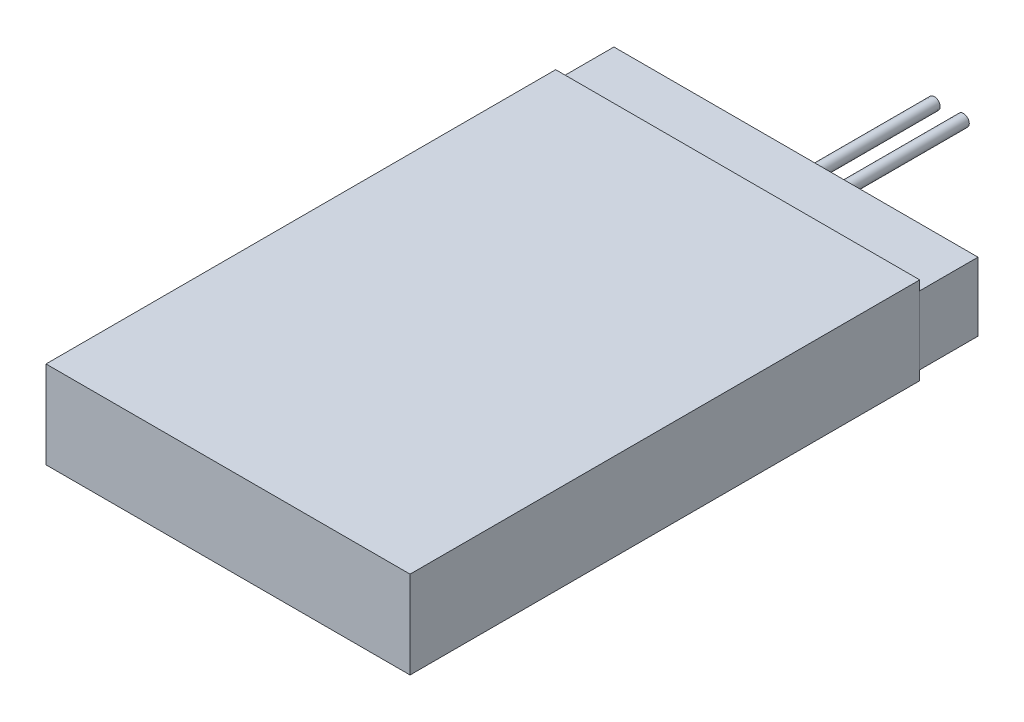
SolidWorks part; units mm, degrees
ref_plane "Front Plane" through (0, 0, 0) normal (0, 0, 1) x (1, 0, 0)
ref_plane "Top Plane" through (0, 0, 0) normal (0, 1, 0) x (1, 0, 0)
ref_plane "Right Plane" through (0, 0, 0) normal (1, 0, 0) x (0, 0, -1)
sketch "Sketch1" plane through (0, 0, 0) normal (0, 1, 0) x (1, 0, 0)
  line L1 (0, 0) -> (25, 0)
  line L2 (0, 0) -> (0, 35)
  line L3 (0, 35) -> (25, 35)
  line L4 (25, 0) -> (25, 35)
  dimension "D1" = 25
  dimension "D2" = 35
extrude "Boss-Extrude1" add sketch "Sketch1" along normal blind 6
sketch "Sketch2" plane through (25, 0, 0) normal (1, 0, 0) x (0, 0, -1)
  line L0 (35, 6) -> (35, 0) construction
  line L1 (35, 5.35) -> (39, 5.35)
  line L2 (35, 5.35) -> (35, 0.65)
  line L3 (35, 0.65) -> (39, 0.65)
  line L4 (39, 5.35) -> (39, 0.65)
  line L5 (0, 0) -> (35, 0) construction
  line L6 (0, 6) -> (35, 6) construction
  dimension "D1" = 4
  dimension "D2" = 0.65
  dimension "D3" = 0.65
extrude "Boss-Extrude2" add sketch "Sketch2" against normal up to surface (25 mm away) separate body up to face at (0, 3, -17.5)
sketch "Sketch3" plane through (0, 0, -39) normal (0, 0, -1) x (-1, 0, 0)
  line L0 (-25, 3) -> (0, 3) construction
  line L1 (-25, 0.65) -> (-25, 5.35) construction
  line L2 (0, 5.35) -> (0, 0.65) construction
  circle A0 centre (-14, 3) radius 0.4
  circle A1 centre (-12, 3) radius 0.4
  dimension "D1" = 0.8
  dimension "D2" = 0.8
  dimension "D3" = 2
  dimension "D4" = 11
extrude "Boss-Extrude3" add sketch "Sketch3" along normal blind 10 separate body
